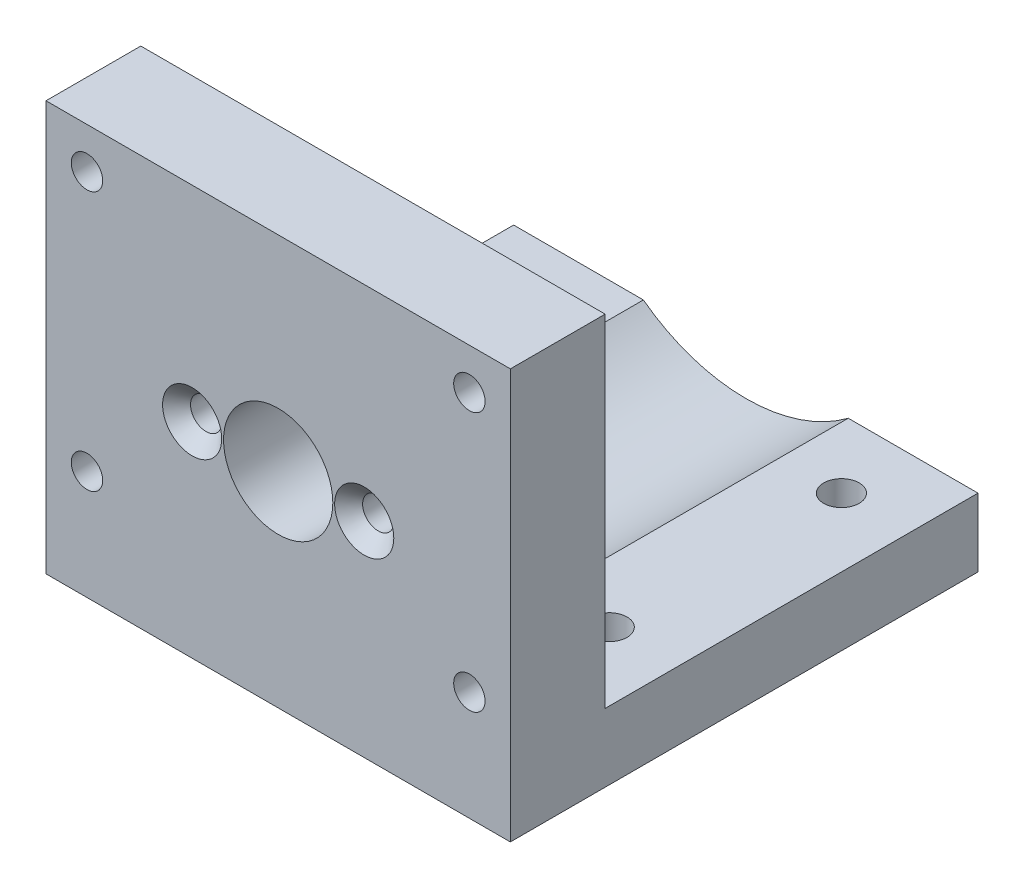
SolidWorks part; units mm, degrees
material "ABS"
ref_plane "Front Plane" through (0, 0, 0) normal (0, 0, 1) x (1, 0, 0)
ref_plane "Top Plane" through (0, 0, 0) normal (0, 1, 0) x (1, 0, 0)
ref_plane "Right Plane" through (0, 0, 0) normal (1, 0, 0) x (0, 0, -1)
sketch "Sketch1" plane through (0, 0, 0) normal (0, 1, 0) x (1, 0, 0)
  line L1 (0, 0) -> (43.18, 0)
  line L2 (0, 0) -> (0, 43.4848)
  line L3 (0, 43.4848) -> (43.18, 43.4848)
  line L4 (43.18, 0) -> (43.18, 43.4848)
  circle A0 centre (6.35, 37.1348) radius 1.651
  circle A1 centre (36.83, 37.1348) radius 1.651
  circle A2 centre (36.83, 15.5448) radius 1.651
  circle A3 centre (6.35, 15.5448) radius 1.651
  dimension "D3" = 21.59
  dimension "D5" = 6.35
  dimension "D7" = 6.35
  dimension "D8" = 6.35
  dimension "D10" = 3.302
  dimension "D11" = 6.35
  dimension "D1" = 43.18
  dimension "D2" = 43.4848
  dimension "D9" = 6.35
extrude "Base leg" add sketch "Sketch1" along normal blind 6.35
sketch "Sketch3" plane through (0, 0, 0) normal (0, 0, 1) x (1, 0, 0)
  line L0 (21.59, 6.35) -> (21.59, 38.1) construction
  line L1 (43.18, 6.35) -> (0, 6.35)
  line L2 (43.18, 6.35) -> (43.18, 38.1)
  line L3 (43.18, 38.1) -> (0, 38.1)
  line L4 (0, 6.35) -> (0, 38.1)
  circle A0 centre (21.59, 19.05) radius 5.08
  circle A1 centre (3.302, 19.05) radius 2.286
  line M6 (43.18, 6.35) -> (0, 6.35)
  dimension "D3" = 10.16
  dimension "D5" = 4.572
  dimension "D6" = 18.288
  dimension "D1" = 43.18
  dimension "D2" = 31.75
  dimension "D7" = 19.05
extrude "Perpendicular leg" add sketch "Sketch3" against normal blind 8.8138 contours A1 | L1 L0 A0 L3 L4 A1 | L0 L2 L3 A0 M6
hole_wizard "CSK for M2.5 Flat Head Machine Screw1" positions "Sketch7" profile "Sketch6" countersink size "M2.5" standard "ANSI Metric" end condition through all
sketch "Sketch7" plane through (0, 0, 0) normal (0, 0, 1) x (1, 0, 0)
  line L0 (21.59, 0) -> (21.59, 38.1) construction
  line L1 (0, 0) -> (43.18, 0) construction
  line L4 (0, 19.05) -> (43.18, 19.05) construction
  line L5 (0, 38.1) -> (0, 0) construction
  line L6 (43.18, 38.1) -> (43.18, 0) construction
  line L7 (43.18, 38.1) -> (0, 38.1) construction
  circle A0 centre (21.59, 19.05) radius 5.08 construction
  circle A1 centre (21.59, 19.05) radius 5.08
  point P0 (13.59, 19.05)
  point P2 (29.59, 19.05)
  dimension "D1" = 16
  dimension "D2" = 8
sketch "Sketch6" plane through (13.59, 19.05, 0) normal (1, 0, 0) x (0, -1, 0)
  line L0 (0, 0) -> (0, 43.4848)
  line L1 (0, 43.4848) -> (1.45, 43.4848)
  line L2 (1.45, 43.4848) -> (1.45, 1.3)
  line L3 (1.45, 1.3) -> (2.75, 0)
  line L5 (2.75, 0) -> (0, 0)
  line L6 (-1.45, 1.3) -> (-2.75, 0) construction
  line L11 (0, -6.35) -> (0, 107.95) construction
  dimension "Thru Hole Dia." = 2.9
  dimension "Thru Hole Depth" = 43.4848
  dimension "Near C'Sink Dia." = 5.5
  dimension "Near C'Sink Angle" = 90
sketch "Sketch10" plane through (0, 0, -8.8138) normal (0, 0, -1) x (-1, 0, 0)
  line L0 (-43.18, 38.1) -> (0, 38.1) construction
  line L1 (-43.18, 6.35) -> (-43.18, 38.1) construction
  line L2 (0, 6.35) -> (0, 38.1) construction
  line L3 (-43.18, 6.35) -> (0, 6.35) construction
  circle A0 centre (-39.37, 34.29) radius 1.4605
  circle A1 centre (-39.37, 10.16) radius 1.4605
  circle A2 centre (-3.81, 34.29) radius 1.4605
  circle A3 centre (-3.81, 10.16) radius 1.4605
  dimension "D3" = 3.81
  dimension "D6" = 2.921
  dimension "D1" = 3.81
  dimension "D2" = 3.81
  dimension "D4" = 3.81
  dimension "D5" = 3.81
extrude "Holes for stabilizing through shaft" cut sketch "Sketch10" against normal through all
sketch "Sketch11" plane through (0, 0, -8.8138) normal (0, 0, -1) x (-1, 0, 0)
  circle A0 centre (-21.59, 19.05) radius 15.875
  dimension "D1" = 31.75
extrude "Cut-Extrude1" cut sketch "Sketch11" along normal through all
